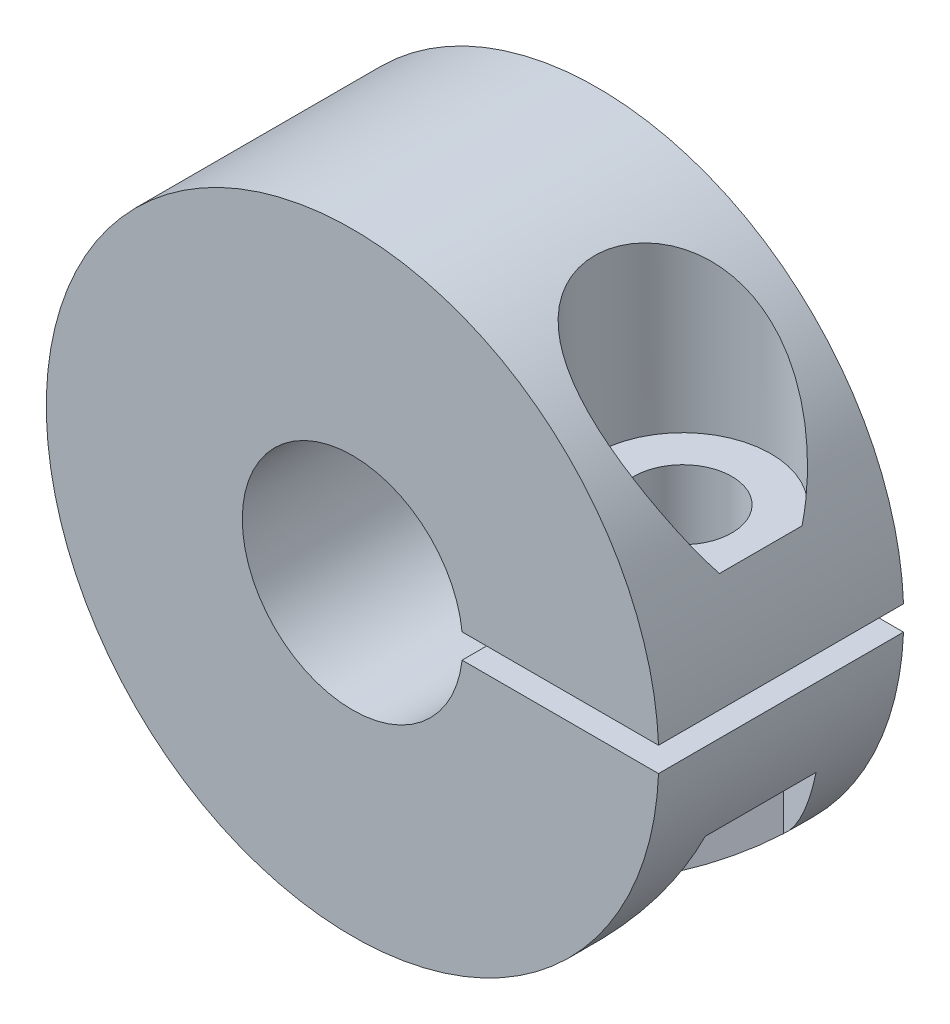
SolidWorks part; units mm, degrees
ref_plane "Front Plane" through (0, 0, 0) normal (0, 0, 1) x (1, 0, 0)
ref_plane "Top Plane" through (0, 0, 0) normal (0, 1, 0) x (1, 0, 0)
ref_plane "Right Plane" through (0, 0, 0) normal (1, 0, 0) x (0, 0, -1)
sketch "Sketch1" plane through (0, 0, 0) normal (0, 0, 1) x (1, 0, 0)
  circle A0 centre (0, 0) radius 4.5
  circle A1 centre (0, 0) radius 12.5
  dimension "D1" = 9
  dimension "D2" = 25
extrude "Boss-Extrude1" add sketch "Sketch1" along normal blind 10
sketch "Sketch2" plane through (0, 0, 10) normal (0, 0, 1) x (1, 0, 0)
  line L1 (3.5059, 0.5) -> (13.4894, 0.5)
  line L2 (3.5059, 0.5) -> (3.5059, -0.5)
  line L3 (3.5059, -0.5) -> (13.4894, -0.5)
  line L4 (13.4894, 0.5) -> (13.4894, -0.5)
  line L5 (3.5059, 0.5) -> (13.4894, -0.5) construction
  line L6 (3.5059, -0.5) -> (13.4894, 0.5) construction
  circle A0 centre (0, 0) radius 4.5 construction
  circle A1 centre (0, 0) radius 12.5 construction
  point P0 (8.4977, 0)
  point P5 (3.5059, 0)
  point P6 (12.4992, 0.1395)
  point P10 (4.4983, -0.1229)
  point P11 (13.4894, 0)
  dimension "D2" = 1
  dimension "D1" = 1
  dimension "D3" = 1
extrude "Cut-Extrude1" cut sketch "Sketch2" against normal through all
sketch "Sketch3" plane through (0, 0, 0) normal (0, 1, 0) x (1, 0, 0)
  line L0 (4.4721, -10) -> (12.49, 0) construction
  line L1 (12.49, 0) -> (12.49, -10) construction
  line L2 (12.49, -10) -> (4.4721, 0) construction
  line L4 (4.4721, -10) -> (12.49, -10)
  line L5 (4.4721, 0) -> (4.4721, -10)
  line L6 (12.49, 0) -> (4.4721, 0)
  line L7 (12.49, -10) -> (12.49, 0)
  line L8 (4.4721, -10) -> (12.49, -10) construction
  line L9 (4.4721, 0) -> (4.4721, -10) construction
  line L10 (12.49, 0) -> (4.4721, 0) construction
  line L11 (12.49, -10) -> (12.49, 0) construction
  circle A0 centre (8.4811, -5) radius 2
  dimension "D2" = 4
  dimension "D1" = 0
extrude "Cut-Extrude2" cut sketch "Sketch3" against normal through all both and the other way through all
ref_plane "Plane1" through (0, 4.5, 0) normal (0, 1, 0) x (1, 0, 0)
sketch "Sketch4" plane through (0, 4.5, 0) normal (0, 1, 0) x (1, 0, 0)
  circle A0 centre (8.4811, -5) radius 3.6
  dimension "D1" = 7.2
extrude "Cut-Extrude3" cut sketch "Sketch4" along normal up to next
ref_plane "Plane2" through (0, -4.5, 0) normal (0, 1, 0) x (1, 0, 0)
sketch "Sketch5" plane through (0, -4.5, 0) normal (0, 1, 0) x (1, 0, 0)
  line L1 (8.4727, -9.0992) -> (12.0269, -7.0568)
  line L2 (12.0269, -7.0568) -> (12.0352, -2.9577)
  line L3 (12.0352, -2.9577) -> (8.4894, -0.9008)
  line L4 (8.4894, -0.9008) -> (4.9353, -2.9432)
  line L5 (4.9353, -2.9432) -> (4.9269, -7.0423)
  line L6 (4.9269, -7.0423) -> (8.4727, -9.0992)
  circle A0 centre (8.4811, -5) radius 3.55 construction
  dimension "D1" = 7.1
extrude "Cut-Extrude4" cut sketch "Sketch5" against normal up to next
